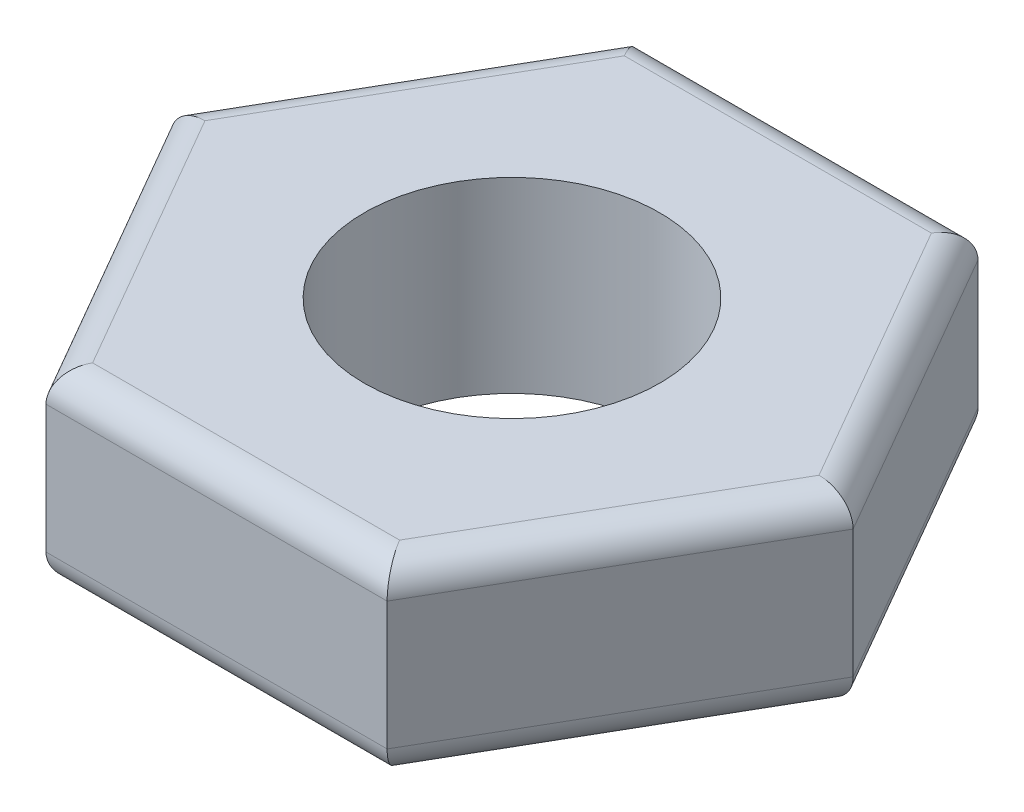
SolidWorks part; units mm, degrees
material "1060 Alloy"
ref_plane "Front Plane" through (0, 0, 0) normal (0, 0, 1) x (1, 0, 0)
ref_plane "Top Plane" through (0, 0, 0) normal (0, 1, 0) x (1, 0, 0)
ref_plane "Right Plane" through (0, 0, 0) normal (1, 0, 0) x (0, 0, -1)
sketch "Sketch1" plane through (0, 0, 0) normal (0, 1, 0) x (1, 0, 0)
  line L1 (1.7321, -3) -> (3.4641, 0)
  line L2 (3.4641, 0) -> (1.7321, 3)
  line L3 (1.7321, 3) -> (-1.7321, 3)
  line L4 (-1.7321, 3) -> (-3.4641, 0)
  line L5 (-3.4641, 0) -> (-1.7321, -3)
  line L6 (-1.7321, -3) -> (1.7321, -3)
  circle A0 centre (0, 0) radius 3 construction
  dimension "D1" = 6
extrude "Boss-Extrude1" add sketch "Sketch1" along normal blind 1.9
sketch "Sketch2" plane through (0, 1.9, 0) normal (0, 1, 0) x (1, 0, 0)
  circle A0 centre (0, 0) radius 1.5
  dimension "D1" = 3
extrude "Cut-Extrude1" cut sketch "Sketch2" against normal blind 2.3
fillet "Fillet1" radius 0.3 12 edges at (-2.5981, 1.9, -1.5) (0, 1.9, -3) (2.5981, 1.9, -1.5) (2.5981, 1.9, 1.5) (0, 1.9, 3) (-2.5981, 1.9, 1.5) (2.5981, 0, 1.5) (2.5981, 0, -1.5) (0, 0, -3) (-2.5981, 0, -1.5) (-2.5981, 0, 1.5) (0, 0, 3)
